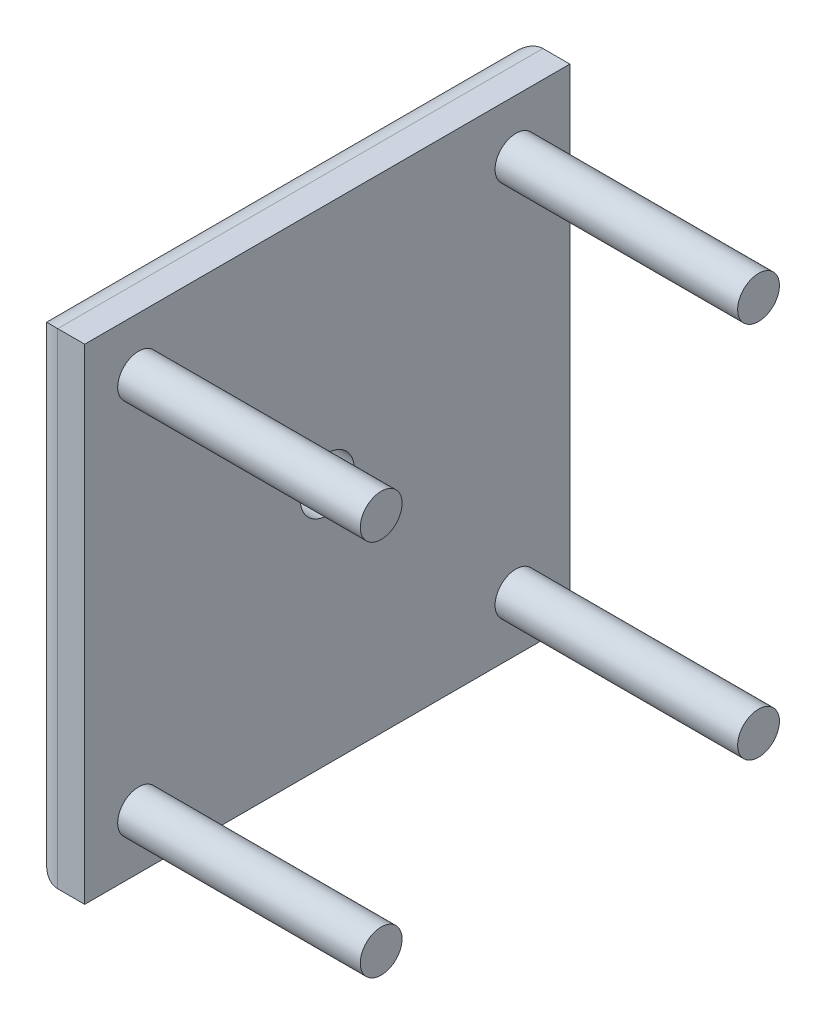
SolidWorks part; units mm, degrees
ref_plane "Front Plane" through (0, 0, 0) normal (0, 0, 1) x (1, 0, 0)
ref_plane "Top Plane" through (0, 0, 0) normal (0, 1, 0) x (1, 0, 0)
ref_plane "Right Plane" through (0, 0, 0) normal (1, 0, 0) x (0, 0, -1)
sketch "Sketch1" plane through (0, 0, 0) normal (1, 0, 0) x (0, 0, -1)
  line L1 (-9, -9) -> (9, -9)
  line L2 (-9, -9) -> (-9, 9)
  line L3 (-9, 9) -> (9, 9)
  line L4 (9, -9) -> (9, 9)
  line L5 (-9, -9) -> (9, 9) construction
  line L6 (-9, 9) -> (9, -9) construction
  line L7 (7, -7) -> (-7, -7) construction
  line L8 (7, -7) -> (7, 7) construction
  line L9 (7, 7) -> (-7, 7) construction
  line L10 (-7, -7) -> (-7, 7) construction
  line L11 (7, -7) -> (-7, 7) construction
  line L12 (7, 7) -> (-7, -7) construction
  circle A0 centre (-7, 7) radius 0.75
  circle A1 centre (7, 7) radius 0.75
  circle A2 centre (7, -7) radius 0.75
  circle A3 centre (-7, -7) radius 0.75
  point P0 (0, 0)
  point P6 (0, 0)
  dimension "D4" = 1.5
  dimension "D1" = 18
  dimension "D2" = 18
  dimension "D3" = 14
extrude "Boss-Extrude1" add sketch "Sketch1" along normal blind 2 contours A1 | L1 L4 L3 L2 A3 A2 A1 A0 | A0 | A3 | A2
sketch "Sketch2" plane through (2, 0, 0) normal (1, 0, 0) x (0, 0, -1)
  line L1 (7, -7) -> (-7, -7) construction
  line L2 (7, -7) -> (7, 7) construction
  line L3 (7, 7) -> (-7, 7) construction
  line L4 (-7, -7) -> (-7, 7) construction
  line L5 (7, -7) -> (-7, 7) construction
  line L6 (7, 7) -> (-7, -7) construction
  circle A0 centre (-7, 7) radius 0.775
  circle A1 centre (-7, -7) radius 0.775
  circle A2 centre (7, -7) radius 0.775
  circle A3 centre (7, 7) radius 0.775
  point P0 (0, 0)
  dimension "D2" = 1.55
  dimension "D1" = 14
extrude "Boss-Extrude2" add sketch "Sketch2" along normal blind 9 contours A0 | A2 | A1 | L2 L1 L4 L3 | A3
sketch "Sketch3" plane through (0, 0, 0) normal (-1, 0, 0) x (0, 0, 1)
  circle A0 centre (0, 0) radius 1
  dimension "D1" = 2
extrude "Cut-Extrude1" cut sketch "Sketch3" against normal blind 9
fillet "Fillet1" [suppressed] radius 10
fillet "Fillet2" radius 1 4 edges at (0, -9, 0) (0, 0, 9) (0, 0, -9) (0, 9, 0)
